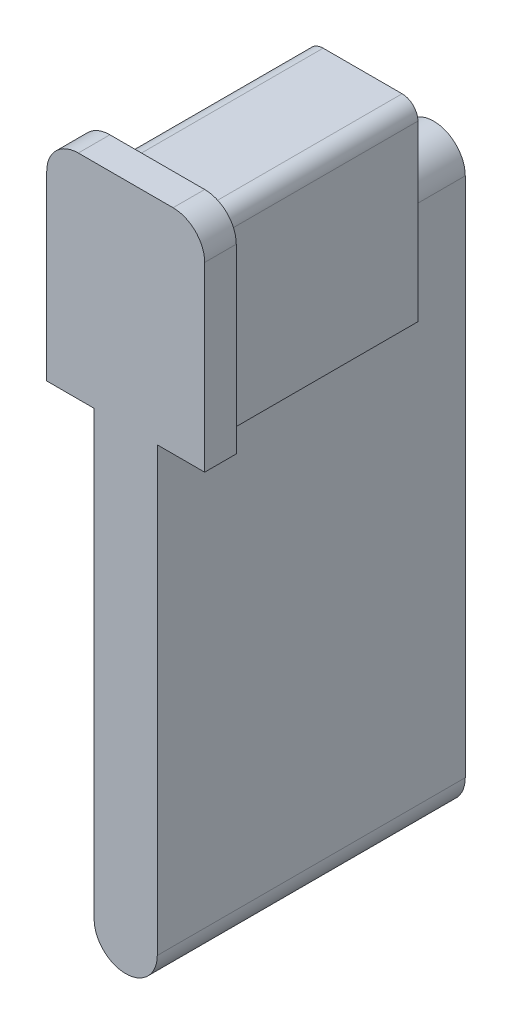
SolidWorks part; units mm, degrees
ref_plane "Plan1" through (0, 0, 0) normal (0, 0, 1) x (1, 0, 0)
ref_plane "Plan2" through (0, 0, 0) normal (0, 1, 0) x (1, 0, 0)
ref_plane "Plan3" through (0, 0, 0) normal (1, 0, 0) x (0, 0, -1)
sketch "Esquisse1" plane through (0, 0, 0) normal (0, 0, 1) x (1, 0, 0)
  line L2 (0, 0) -> (0, 33)
  line L4 (4, 0) -> (4, 33)
  arc A0 (4, 33) -> (0, 33) centre (2, 33) ccw
  arc A1 (0, 0) -> (4, 0) centre (2, 0) ccw
extrude "Base-Extrusion" add sketch "Esquisse1" along normal blind 19.5
sketch "Esquisse2" plane through (0, 0, 19.5) normal (0, 0, 1) x (1, 0, 0)
  line L1 (-1.5, 40) -> (5.5, 40)
  line L2 (-1.5, 40) -> (-1.5, 28)
  line L3 (-1.5, 28) -> (5.5, 28)
  line L4 (5.5, 40) -> (5.5, 28)
extrude "Boss.-Extru.1" add sketch "Esquisse2" against normal blind 15
fillet "Congé1" radius 1
sketch "Esquisse3" plane through (0, 0, 19.5) normal (0, 0, 1) x (1, 0, 0)
  line L1 (-3, 41.5) -> (7, 41.5)
  line L2 (-3, 41.5) -> (-3, 28)
  line L3 (-3, 28) -> (7, 28)
  line L4 (7, 41.5) -> (7, 28)
extrude "Boss.-Extru.2" add sketch "Esquisse3" against normal blind 2
fillet "Congé2" radius 2
